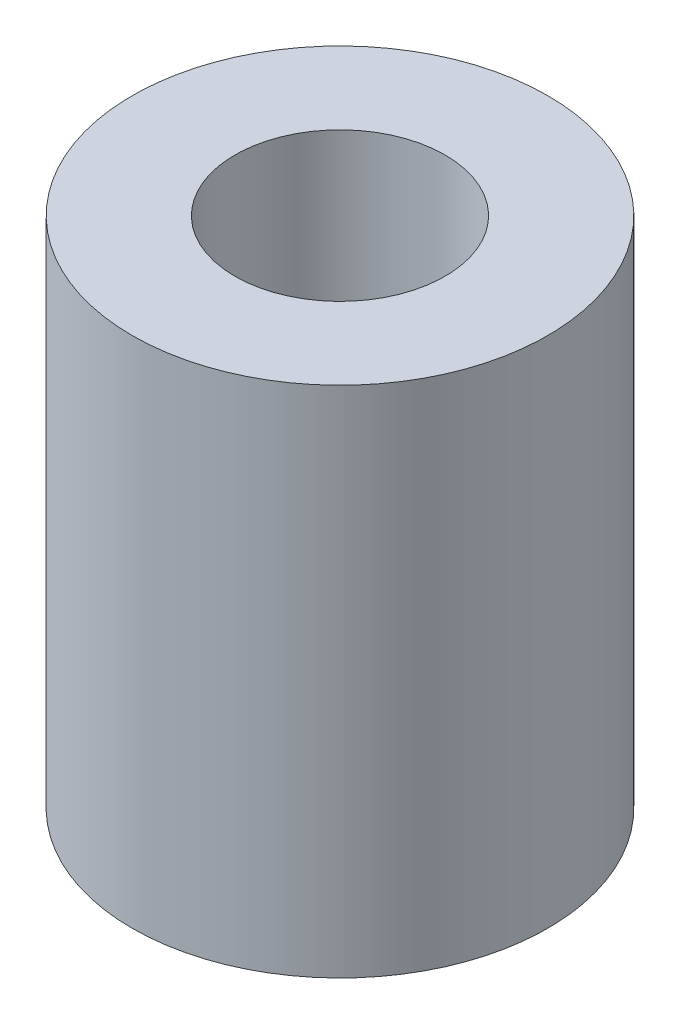
SolidWorks part; units mm, degrees
ref_plane "Front Plane" through (0, 0, 0) normal (0, 0, 1) x (1, 0, 0)
ref_plane "Top Plane" through (0, 0, 0) normal (0, 1, 0) x (1, 0, 0)
ref_plane "Right Plane" through (0, 0, 0) normal (1, 0, 0) x (0, 0, -1)
sketch "5mm" plane through (0, 0, 0) normal (0, 1, 0) x (1, 0, 0)
  circle A0 centre (0, 0) radius 2.6
  circle A1 centre (0, 0) radius 5.14
  dimension "D1" = 5.2
  dimension "D2" = 2.54
extrude "Boss-Extrude1" add sketch "5mm" along normal blind 12.7
